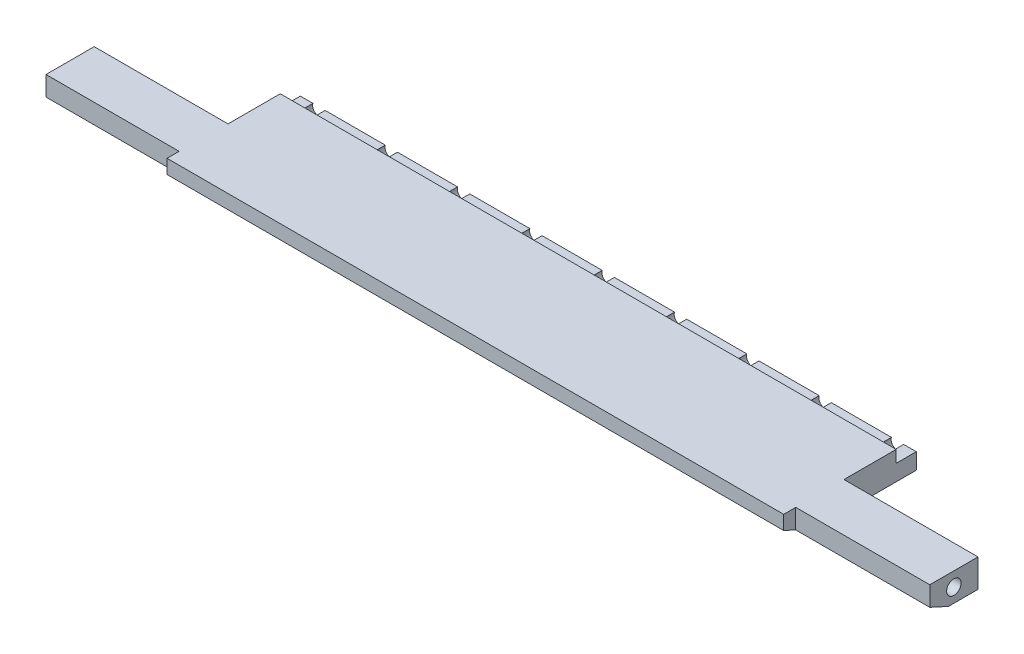
SolidWorks part; units mm, degrees
ref_plane "Спереди" through (0, 0, 0) normal (0, 0, 1) x (1, 0, 0)
ref_plane "Сверху" through (0, 0, 0) normal (0, 1, 0) x (1, 0, 0)
ref_plane "Справа" through (0, 0, 0) normal (1, 0, 0) x (0, 0, -1)
sketch "Эскиз1" plane through (0, 0, 0) normal (0, 0, 1) x (1, 0, 0)
  line L0 (-1000, 3.5) -> (49000, 3.5) construction
  line L1 (0, 0) -> (220, 0)
  line L2 (0, 0) -> (0, 7)
  line L3 (0, 7) -> (220, 7)
  line L4 (220, 0) -> (220, 7)
  circle A0 centre (37.97, 3.5) radius 1.6
  circle A9 centre (55.97, 3.5) radius 1.6
  circle A10 centre (73.97, 3.5) radius 1.6
  circle A11 centre (91.97, 3.5) radius 1.6
  circle A12 centre (109.97, 3.5) radius 1.6
  circle A13 centre (127.97, 3.5) radius 1.6
  circle A14 centre (145.97, 3.5) radius 1.6
  circle A15 centre (163.97, 3.5) radius 1.6
  circle A16 centre (181.97, 3.5) radius 1.6
  point P26 (0, 3.5)
  dimension "D3" = 3.2
  dimension "D6" = 38.03
  dimension "D7" = 14.8
  dimension "D8" = 18
  dimension "D1" = 7
  dimension "D2" = 220
  dimension "D4" = 37.97
  dimension "D5" = 9
extrude "Бобышка-Вытянуть1" add sketch "Эскиз1" along normal blind 30
sketch "Эскиз2" plane through (0, 7, 0) normal (0, 1, 0) x (1, 0, 0)
  line L0 (220, -30) -> (220, 0) construction
  line L1 (0, 0) -> (220, 0)
  line L2 (0, 0) -> (0, -5)
  line L3 (0, -5) -> (220, -5)
  line L4 (220, 0) -> (220, -5)
  dimension "D1" = 5
extrude "Вырез-Вытянуть1" cut sketch "Эскиз2" against normal blind 3
sketch "Эскиз3" plane through (0, 7, 0) normal (0, 1, 0) x (1, 0, 0)
  line L5 (0, -18) -> (33.3087, -18)
  line L6 (0, -18) -> (0, 0)
  line L7 (0, 0) -> (33.3087, 0)
  line L8 (33.3087, -18) -> (33.3087, 0)
  line L14 (220, -18) -> (186.6313, -18)
  line L15 (220, -18) -> (220, 0)
  line L16 (220, 0) -> (186.6313, 0)
  line L17 (186.6313, -18) -> (186.6313, 0)
  dimension "D3" = 18
  dimension "D4" = 18
extrude "Вырез-Вытянуть2" cut sketch "Эскиз3" against normal through all
sketch "Эскиз6" plane through (0, 0, 30) normal (0, 0, 1) x (1, 0, 0)
  line L0 (220, 7) -> (0, 7) construction
  line L1 (33.1361, 7) -> (186.6313, 7)
  line L2 (33.1361, 7) -> (33.1361, 0)
  line L3 (33.1361, 0) -> (186.6313, 0)
  line L4 (186.6313, 7) -> (186.6313, 0)
extrude "Бобышка-Вытянуть2" add sketch "Эскиз6" along normal blind 3
sketch "Эскиз7" plane through (0, 0, 0) normal (-1, 0, 0) x (0, 0, 1)
  line L0 (18, 0) -> (18, 7) construction
  line L1 (30, 0) -> (18, 0) construction
  circle A0 centre (24, 3.5) radius 1.8
  dimension "D1" = 3.6
  dimension "D2" = 6
  dimension "D3" = 3.5
extrude "Вырез-Вытянуть3" cut sketch "Эскиз7" against normal blind 10
sketch "Эскиз8" plane through (220, 0, 0) normal (1, 0, 0) x (0, 0, -1)
  line L0 (-30, 7) -> (-18, 7) construction
  line L1 (-30, 0) -> (-30, 7) construction
  circle A0 centre (-24, 3.5) radius 1.8
  dimension "D1" = 3.6
  dimension "D2" = 3.5
  dimension "D3" = 6
extrude "Вырез-Вытянуть4" cut sketch "Эскиз8" against normal blind 10
sketch "Эскиз9" plane through (220, 0, 0) normal (1, 0, 0) x (0, 0, -1)
  line L0 (-33, 0) -> (-33, 3.5)
  line L1 (-33, 0) -> (-33, 7) construction
  line L2 (-33, 3.5) -> (-25.3494, 0)
  line L3 (-30, 0) -> (-18, 0) construction
  line L4 (-25.3494, 0) -> (-33, 0)
  point P5 (-25.3494, 0)
extrude "Вырез-Вытянуть5" cut sketch "Эскиз9" against normal through all
